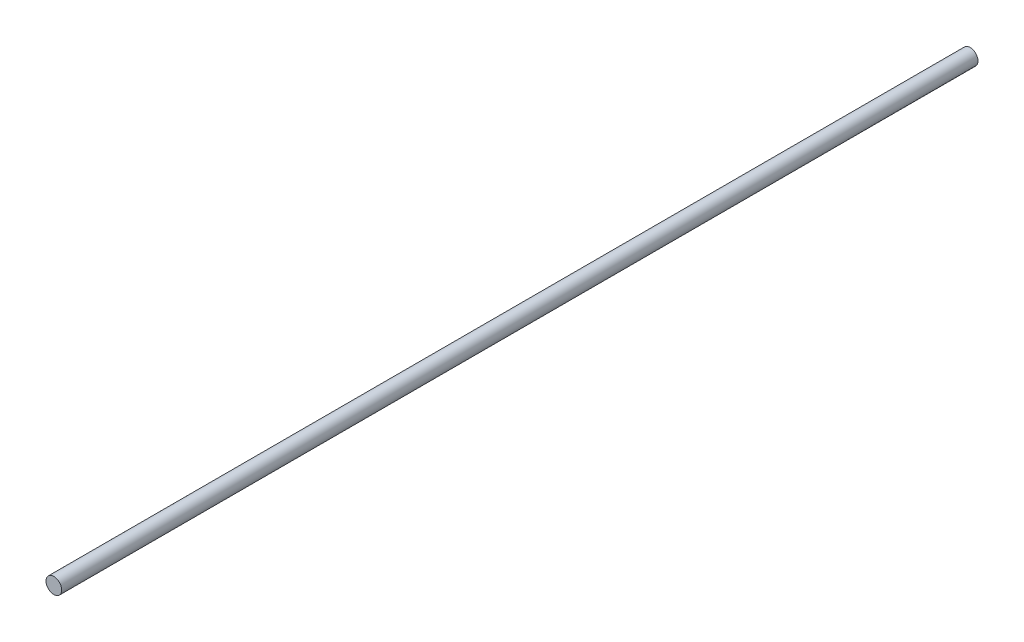
SolidWorks part; units mm, degrees
ref_plane "Front Plane" through (0, 0, 0) normal (0, 0, 1) x (1, 0, 0)
ref_plane "Top Plane" through (0, 0, 0) normal (0, 1, 0) x (1, 0, 0)
ref_plane "Right Plane" through (0, 0, 0) normal (1, 0, 0) x (0, 0, -1)
sketch "Sketch1" plane through (0, 0, 0) normal (0, 0, 1) x (1, 0, 0)
  circle A0 centre (0, 0) radius 3
  dimension "D1" = 6
extrude "Boss-Extrude1" add sketch "Sketch1" along normal blind 350
